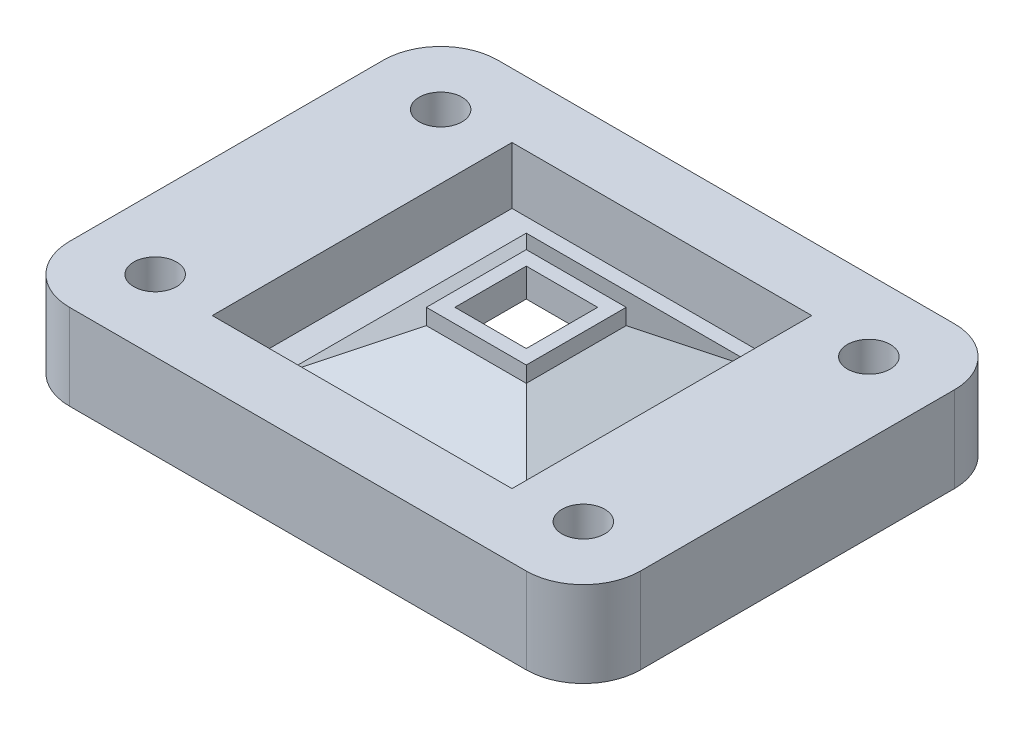
SolidWorks part; units mm, degrees
ref_plane "Front" through (0, 0, 0) normal (0, 0, 1) x (1, 0, 0)
ref_plane "Top" through (0, 0, 0) normal (0, 1, 0) x (1, 0, 0)
ref_plane "Right" through (0, 0, 0) normal (1, 0, 0) x (0, 0, -1)
sketch "Sketch1" plane through (0, 0, 0) normal (0, 1, 0) x (1, 0, 0)
  line L1 (0, 0) -> (40, 0)
  line L2 (0, 0) -> (0, 30)
  line L3 (0, 30) -> (40, 30)
  line L4 (40, 0) -> (40, 30)
  dimension "D1" = 40
  dimension "D2" = 30
extrude "Boss-Extrude1" add sketch "Sketch1" along normal blind 6
sketch "Sketch2" plane through (0, 6, 0) normal (0, 1, 0) x (1, 0, 0)
  line L0 (20, 30) -> (20, 0) construction
  line L1 (40, 30) -> (0, 30) construction
  line L2 (0, 0) -> (40, 0) construction
  line L3 (0, 15) -> (40, 15) construction
  line L4 (0, 30) -> (0, 0) construction
  line L5 (40, 0) -> (40, 30) construction
  circle A0 centre (5, 5) radius 1.5
  circle A1 centre (5, 25) radius 1.5
  circle A2 centre (35, 5) radius 1.5
  circle A3 centre (35, 25) radius 1.5
  dimension "D1" = 3
  dimension "D2" = 5
  dimension "D3" = 5
extrude "Cut-Extrude1" cut sketch "Sketch2" against normal up to surface (6 mm away) up to face at (20, 0, -15)
fillet "Fillet1" radius 4 4 edges at (0, 3, -30) (40, 3, -30) (40, 3, 0) (0, 3, 0)
sketch "Sketch3" plane through (0, 6, 0) normal (0, 1, 0) x (1, 0, 0)
  line L0 (4, 0) -> (36, 0) construction
  line L1 (9.5, 4.5) -> (30.5, 4.5)
  line L2 (9.5, 4.5) -> (9.5, 25.5)
  line L3 (9.5, 25.5) -> (30.5, 25.5)
  line L4 (30.5, 4.5) -> (30.5, 25.5)
  line L5 (0, 26) -> (0, 4) construction
  point P4 (20, 4.5)
  point P7 (20, 0)
  point P8 (9.5, 15)
  point P11 (0, 15)
  dimension "D1" = 21
  dimension "D2" = 21
extrude "Cut-Extrude2" cut sketch "Sketch3" against normal blind 4
sketch "Sketch6" plane through (0, 2, 0) normal (0, 1, 0) x (1, 0, 0)
  line L0 (9.5, 25.5) -> (9.5, 4.5) construction
  line L1 (17.5, 13.5) -> (22.5, 13.5)
  line L2 (17.5, 13.5) -> (17.5, 18.5)
  line L3 (17.5, 18.5) -> (22.5, 18.5)
  line L4 (22.5, 13.5) -> (22.5, 18.5)
  line L5 (30.5, 25.5) -> (9.5, 25.5) construction
  line L6 (30.5, 4.5) -> (30.5, 25.5) construction
  line L7 (9.5, 4.5) -> (30.5, 4.5) construction
  dimension "D1" = 8
  dimension "D2" = 8
  dimension "D3" = 9
  dimension "D4" = 7
extrude "Cut-Extrude3" cut sketch "Sketch6" against normal up to surface (2 mm away) up to face at (5, 0, -26.5)
sketch "Sketch7" plane through (0, 2, 0) normal (0, 1, 0) x (1, 0, 0)
  line L5 (17.5, 18.5) -> (22.5, 18.5)
  line L6 (17.5, 18.5) -> (17.5, 13.5)
  line L7 (17.5, 13.5) -> (22.5, 13.5)
  line L8 (16.5, 12.5) -> (23.5, 12.5)
  line L9 (23.5, 12.5) -> (23.5, 19.5)
  line L10 (23.5, 19.5) -> (16.5, 19.5)
  line L11 (16.5, 19.5) -> (16.5, 12.5)
  line L12 (16.5, 12.5) -> (23.5, 12.5)
  line L13 (23.5, 12.5) -> (23.5, 19.5)
  line L14 (23.5, 19.5) -> (16.5, 19.5)
  line L15 (16.5, 19.5) -> (16.5, 12.5)
  line L16 (22.5, 18.5) -> (22.5, 13.5)
  dimension "D1" = 1
extrude "Boss-Extrude2" add sketch "Sketch7" along normal blind 4
chamfer "Chamfer1" distance 4 angle 60 4 edges at (17.5, 0, -16) (20, 0, -13.5) (22.5, 0, -16) (20, 0, -18.5)
chamfer "Chamfer2" distance 5 angle 30 4 edges at (16.5, 2, -16) (20, 2, -19.5) (23.5, 2, -16) (20, 2, -12.5)
